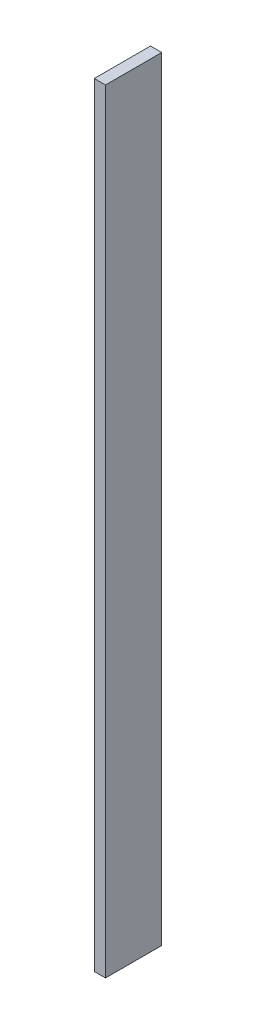
SolidWorks part; units mm, degrees
ref_plane "Front" through (0, 0, 0) normal (0, 0, 1) x (1, 0, 0)
ref_plane "Top" through (0, 0, 0) normal (0, 1, 0) x (1, 0, 0)
ref_plane "Right" through (0, 0, 0) normal (1, 0, 0) x (0, 0, -1)
sketch "Sketch1" plane through (0, 0, 0) normal (0, 1, 0) x (1, 0, 0)
  line L1 (-9.9715, -25.104) -> (0.1885, -25.104)
  line L2 (-9.9715, -25.104) -> (-9.9715, 25.696)
  line L3 (-9.9715, 25.696) -> (0.1885, 25.696)
  line L4 (0.1885, -25.104) -> (0.1885, 25.696)
  line L5 (-9.9715, -25.104) -> (0.1885, 25.696) construction
  line L6 (-9.9715, 25.696) -> (0.1885, -25.104) construction
  point P0 (-4.8915, 0.296)
extrude "Boss-Extrude1" add sketch "Sketch1" along normal blind 698.5
